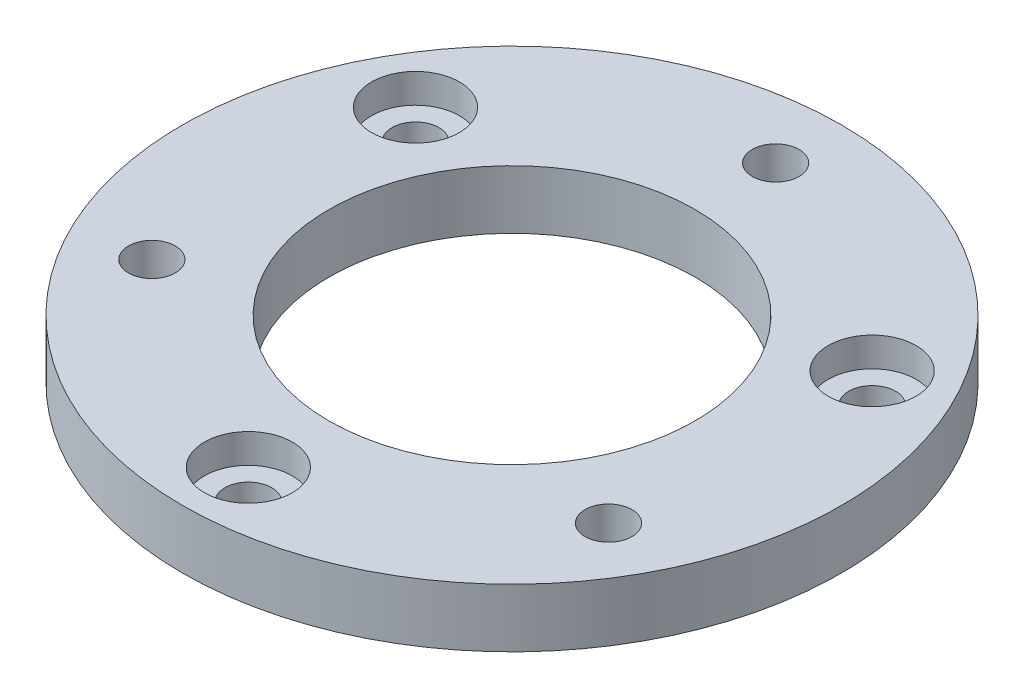
SolidWorks part; units mm, degrees
ref_plane "Front Plane" through (0, 0, 0) normal (0, 0, 1) x (1, 0, 0)
ref_plane "Top Plane" through (0, 0, 0) normal (0, 1, 0) x (1, 0, 0)
ref_plane "Right Plane" through (0, 0, 0) normal (1, 0, 0) x (0, 0, -1)
sketch "Sketch1" plane through (0, 0, 0) normal (0, 1, 0) x (1, 0, 0)
  circle A0 centre (0, 0) radius 22.5
  circle A1 centre (0, 18) radius 1.6
  circle A2 centre (15.5885, 9) radius 1.6
  circle A3 centre (15.5885, -9) radius 1.6
  circle A4 centre (0, -18) radius 1.6
  circle A5 centre (-15.5885, -9) radius 1.6
  circle A6 centre (-15.5885, 9) radius 1.6
  circle A7 centre (0, 0) radius 12.5
  point P6 (0, 0)
  point P18 (0, 0)
  dimension "D1" = 3.2
  dimension "D3" = 45
  dimension "D5" = 25
  dimension "D2" = 18
  dimension "D8" = 60
  dimension "D9" = 18
  dimension "D4" = 6
extrude "Boss-Extrude1" add sketch "Sketch1" along normal blind 4
sketch "Sketch2" plane through (0, 4, 0) normal (0, 1, 0) x (1, 0, 0)
  circle A0 centre (-15.5885, 9) radius 3
  circle A1 centre (15.5885, 9) radius 3
  circle A2 centre (0, -18) radius 3
  dimension "D1" = 6
  dimension "D2" = 6
  dimension "D3" = 6
extrude "Cut-Extrude1" cut sketch "Sketch2" against normal blind 2
